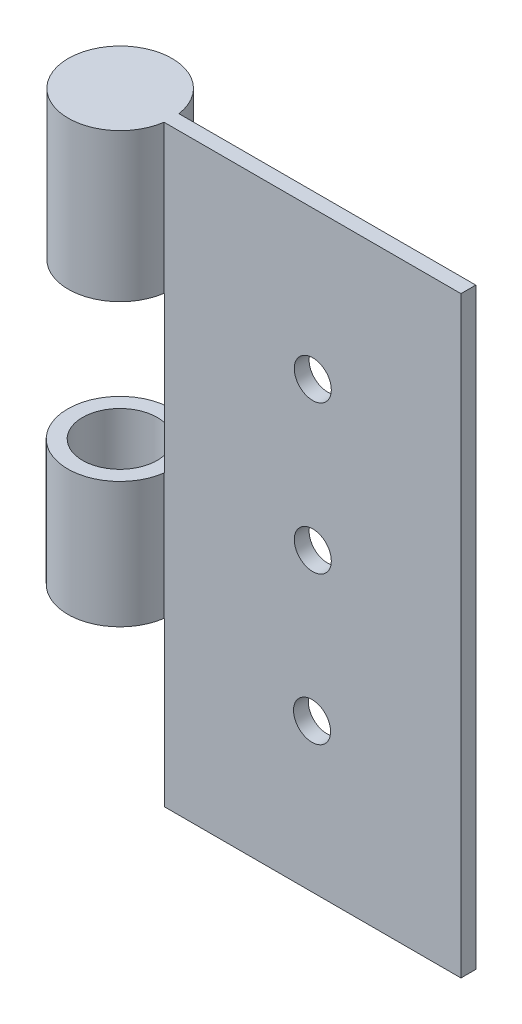
SolidWorks part; units mm, degrees
material "AISI 1020"
ref_plane "Front Plane" through (0, 0, 0) normal (0, 0, 1) x (1, 0, 0)
ref_plane "Top Plane" through (0, 0, 0) normal (0, 1, 0) x (1, 0, 0)
ref_plane "Right Plane" through (0, 0, 0) normal (1, 0, 0) x (0, 0, -1)
sketch "Sketch1" plane through (0, 0, 0) normal (0, 0, 1) x (1, 0, 0)
  line L1 (0, 0) -> (50.8, 0)
  line L2 (0, 0) -> (0, 101.6)
  line L3 (0, 101.6) -> (50.8, 101.6)
  line L4 (50.8, 0) -> (50.8, 101.6)
  dimension "D1" = 50.8
  dimension "D2" = 101.6
extrude "Boss-Extrude2" add sketch "Sketch1" against normal blind 2.54
hole_wizard "1/4 (0.25) Diameter Hole1" positions "3DSketch1" profile "Sketch3" hole size "1/4" standard "ANSI Inch" end condition through all
sketch3d "3DSketch1"
  line L0 (50.8, 101.6, 0) -> (0, 101.6, 0) construction
  line L1 (0, 0, 0) -> (50.8, 0, 0) construction
  line L2 (0, 101.6, -2.54) -> (0, 0, -2.54) construction
  line L3 (0, 101.6, 0) -> (0, 0, 0) construction
  point P0 (25.4, 76.2, 0)
  point P6 (25.2727, 25.4, 0)
  point P16 (25.4, 50.8, 0)
  dimension "D1" = 25.4
  dimension "D2" = 25.4
  dimension "D3" = 25.4
  dimension "D4" = 25.4
  dimension "D5" = 25.4
  dimension "D6" = 50.8
sketch "Sketch3" plane through (25.4, 76.2, 0) normal (1, 0, 0) x (0, -1, 0)
  line L0 (0, 0) -> (0, 2.54)
  line L1 (0, 2.54) -> (3.175, 2.54)
  line L2 (3.175, 2.54) -> (3.175, 0)
  line L5 (3.175, 0) -> (0, 0)
  line L11 (0, -6.35) -> (0, 107.95) construction
  dimension "Thru Hole Dia." = 6.35
  dimension "Thru Hole Depth" = 2.54
ref_plane "Plane1" through (0, 0, -1.27) normal (0, 0, 1) x (1, 0, 0)
sketch "Sketch5" plane through (0, 0, -1.27) normal (0, 0, 1) x (1, 0, 0)
  line L0 (0, 101.6) -> (-2.54, 101.6)
  line L1 (-2.54, 101.6) -> (-2.54, 76.2)
  line L2 (-2.54, 76.2) -> (0, 76.2)
  line L3 (0, 101.6) -> (0, 0) construction
  line L4 (0, 76.2) -> (0, 101.6)
  line L5 (0, 0) -> (-8.89, 0) construction
  line L6 (-8.89, 0) -> (-8.89, 101.6) construction
  line L7 (-8.89, 101.6) -> (0, 101.6) construction
  dimension "D1" = 25.4
  dimension "D2" = 2.54
  dimension "D3" = 8.89
revolve "Revolve2" add sketch "Sketch5" angle 360 about L6
sketch "Sketch6" plane through (0, 0, 0) normal (-1, 0, 0) x (0, 0, 1)
  line L0 (0, 76.2) -> (-2.54, 76.2)
  line L4 (0, 0) -> (0, 101.6)
  line L5 (0, 101.6) -> (-2.54, 101.6)
  line L6 (-2.54, 101.6) -> (-2.54, 0)
  line L7 (-2.54, 0) -> (0, 0)
  line L8 (0, 76.2) -> (0, 101.6)
  line L9 (0, 101.6) -> (-2.54, 101.6)
  line L10 (-2.54, 101.6) -> (-2.54, 76.2)
  dimension "D2" = 25.4
  dimension "D1" = 0
extrude "Boss-Extrude3" add sketch "Sketch6" along normal up to next
sketch "Sketch7" plane through (0, 0, -1.27) normal (0, 0, 1) x (1, 0, 0)
  line L0 (0, 49.53) -> (0, 27.94)
  line L1 (0, 76.2) -> (0, 0) construction
  line L2 (0, 27.94) -> (-2.54, 27.94)
  line L3 (-2.54, 27.94) -> (-2.54, 49.53)
  line L4 (-2.54, 49.53) -> (0, 49.53)
  line L5 (50.8, 101.6) -> (-0.0912, 101.6) construction
  line L6 (-0.0912, 101.6) -> (-8.9356, 101.6) construction
  line L7 (-0.0912, 101.6) -> (-17.78, 101.6) construction
  line L8 (-8.9356, 101.6) -> (-8.9356, 0) construction
  line L9 (-8.9356, 0) -> (0, 0) construction
  dimension "D1" = 2.54
  dimension "D2" = 21.59
  dimension "D3" = 52.07
revolve "Revolve3" add sketch "Sketch7" angle 360 about L8
sketch "Sketch8" plane through (0, 0, 0) normal (-1, 0, 0) x (0, 0, 1)
  line L0 (-2.54, 27.94) -> (0, 27.94)
  line L1 (-2.54, 49.53) -> (0, 49.53)
  line L2 (5.1256, 49.53) -> (-7.6656, 49.53) construction
  line L3 (-10.2056, 27.94) -> (7.6656, 27.94) construction
  line L4 (0, 76.2) -> (-2.54, 76.2)
  line L5 (-2.54, 76.2) -> (-2.54, 0)
  line L6 (-2.54, 0) -> (0, 0)
  line L7 (0, 0) -> (0, 76.2)
  line L9 (-2.54, 49.53) -> (-2.54, 27.94)
  line L11 (0, 27.94) -> (0, 49.53)
  dimension "D2" = 0
  dimension "D3" = 0
  dimension "D1" = 0
extrude "Boss-Extrude4" add sketch "Sketch8" along normal up to next
sketch "Sketch9" plane through (0, 101.6, 0) normal (0, 1, 0) x (1, 0, 0)
  circle A0 centre (-8.89, 1.27) radius 6.35 construction
  circle A1 centre (-8.89, 1.27) radius 6.35
extrude "Boss-Extrude5" add sketch "Sketch9" against normal blind 2.54
